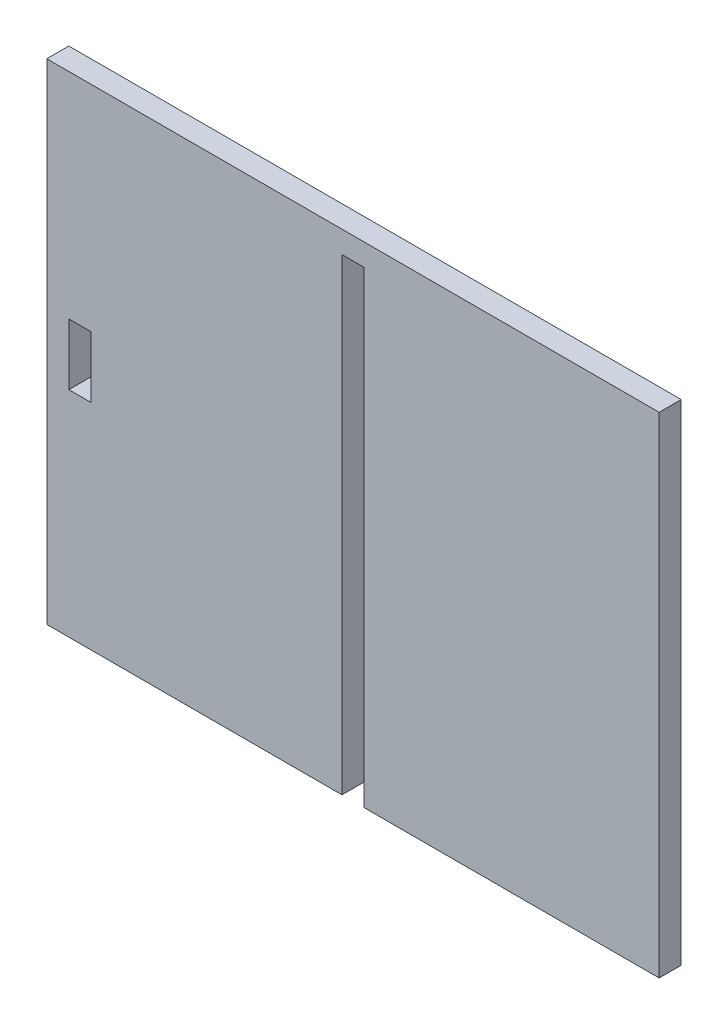
SolidWorks part; units mm, degrees
ref_plane "Front Plane" through (0, 0, 0) normal (0, 0, 1) x (1, 0, 0)
ref_plane "Top Plane" through (0, 0, 0) normal (0, 1, 0) x (1, 0, 0)
ref_plane "Right Plane" through (0, 0, 0) normal (1, 0, 0) x (0, 0, -1)
sketch "Sketch1" plane through (0, 0, 0) normal (0, 0, 1) x (1, 0, 0)
  line L0 (2.2317, -200) -> (243.2317, -200)
  line L1 (-256.7683, 200) -> (243.2317, 200)
  line L2 (-256.7683, 200) -> (-256.7683, -200)
  line L3 (-256.7683, -200) -> (-15.7683, -200)
  line L4 (243.2317, 200) -> (243.2317, -200)
  line L5 (-256.7683, 200) -> (-15.7683, 12.2822) construction
  line L6 (-256.7683, -200) -> (-15.7683, -12.2822) construction
  line L7 (-15.7683, 182) -> (2.2317, 182)
  line L8 (-15.7683, 182) -> (-15.7683, -200)
  line L10 (2.2317, 182) -> (2.2317, -200)
  line L11 (0, 0) -> (2.2317, 1.7383) construction
  line L12 (0, 0) -> (2.2317, -1.7383) construction
  line L13 (0, 0) -> (-256.7683, 0) construction
  line L15 (-238.7683, 25) -> (-220.7683, 25)
  line L16 (-238.7683, 25) -> (-238.7683, -25)
  line L17 (-238.7683, -25) -> (-220.7683, -25)
  line L18 (-220.7683, 25) -> (-220.7683, -25)
  line L19 (-238.7683, 25) -> (-220.7683, -25) construction
  line L20 (-238.7683, -25) -> (-220.7683, 25) construction
  point P0 (0, 0)
  point P15 (-229.7683, 0)
  dimension "D1" = 500
  dimension "D2" = 400
  dimension "D3" = 18
  dimension "D4" = 18
  dimension "D5" = 241
  dimension "D6" = 241
  dimension "D7" = 18
  dimension "D8" = 18
  dimension "D9" = 241
  dimension "D10" = 18
  dimension "D11" = 50
extrude "Boss-Extrude1" add sketch "Sketch1" along normal blind 18
